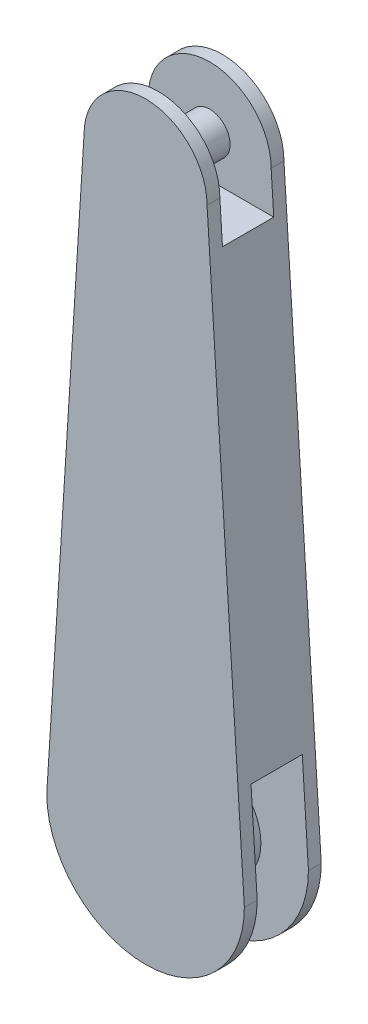
SolidWorks part; units mm, degrees
ref_plane "Front Plane" through (0, 0, 0) normal (0, 0, 1) x (1, 0, 0)
ref_plane "Top Plane" through (0, 0, 0) normal (0, 1, 0) x (1, 0, 0)
ref_plane "Right Plane" through (0, 0, 0) normal (1, 0, 0) x (0, 0, -1)
sketch "Sketch2" plane through (0, 0, 0) normal (0, 0, 1) x (1, 0, 0)
  line L0 (120, 1342.75) -> (192.75, 192.75)
  line L1 (-120, 1342.75) -> (-192.75, 192.75)
  arc A0 (-192.75, 192.75) -> (192.75, 192.75) centre (0, 192.75) ccw
  arc A1 (120, 1342.75) -> (-120, 1342.75) centre (0, 1342.75) ccw
extrude "Boss-Extrude1" add sketch "Sketch2" along normal mid plane 150 contours L0 A0 L1 A1
sketch "Sketch3" plane through (0, 0, 0) normal (1, 0, 0) x (0, 0, -1)
  line L0 (-75, 0) -> (75, 0) construction
  line L1 (50, 0) -> (-50, 0)
  line L2 (50, 0) -> (50, 382.75)
  line L3 (50, 382.75) -> (-50, 382.75)
  line L4 (-50, 0) -> (-50, 382.75)
  line L5 (75, 1462.75) -> (-75, 1462.75) construction
  line L6 (50, 1462.75) -> (-50, 1462.75)
  line L7 (50, 1462.75) -> (50, 1262.75)
  line L8 (50, 1262.75) -> (-50, 1262.75)
  line L9 (-50, 1462.75) -> (-50, 1262.75)
extrude "Cut-Extrude1" cut sketch "Sketch3" against normal mid plane 390
sketch "Sketch4" plane through (0, 0, 50) normal (0, 0, -1) x (-1, 0, 0)
  circle A0 centre (0, 192.75) radius 100
sketch "Sketch5" plane through (0, 0, 50) normal (0, 0, -1) x (-1, 0, 0)
  circle A0 centre (0, 1342.75) radius 40
extrude "Boss-Extrude2" add sketch "Sketch5" along normal blind 100
extrude "Boss-Extrude3" add sketch "Sketch4" along normal blind 100 contours A0
